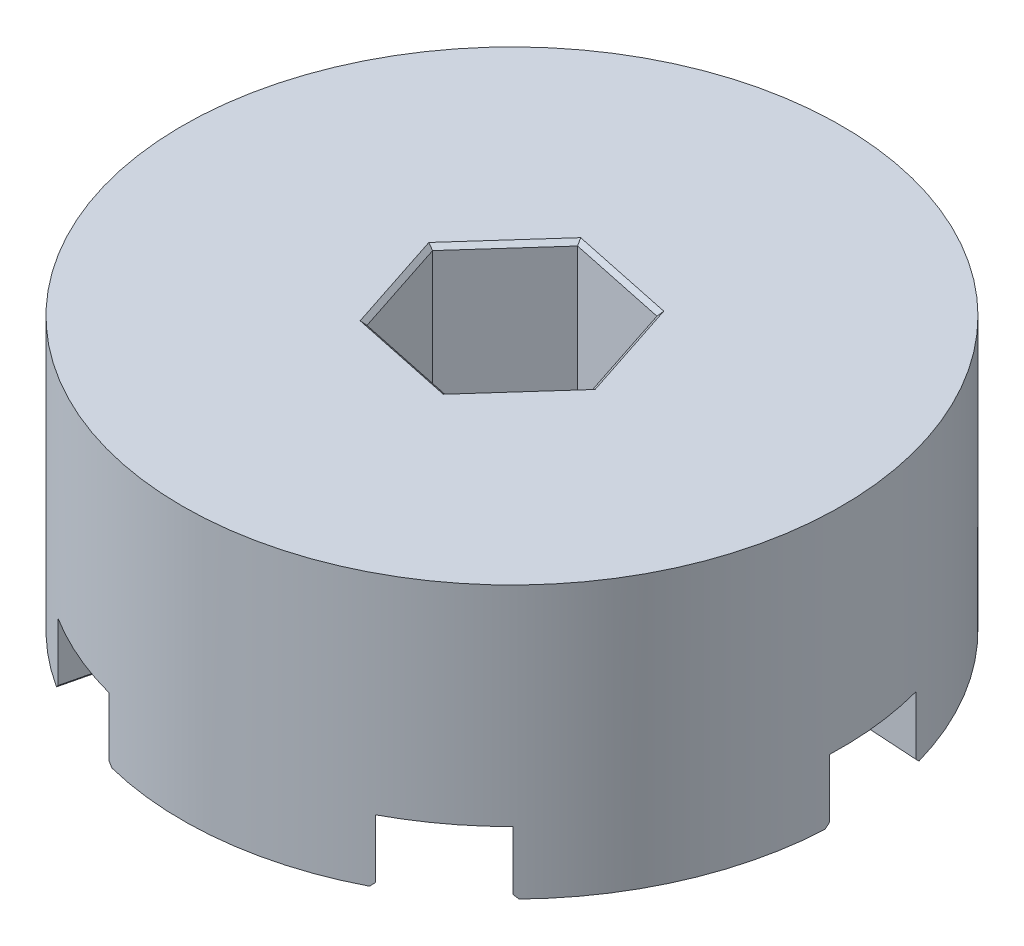
SolidWorks part; units mm, degrees
ref_plane "Front Plane" through (0, 0, 0) normal (0, 0, 1) x (1, 0, 0)
ref_plane "Top Plane" through (0, 0, 0) normal (0, 1, 0) x (1, 0, 0)
ref_plane "Right Plane" through (0, 0, 0) normal (1, 0, 0) x (0, 0, -1)
sketch "Sketch1" plane through (0, 0, 0) normal (0, 1, 0) x (1, 0, 0)
  circle A0 centre (0, 0) radius 15.75
  dimension "D1" = 31.5
extrude "Boss-Extrude1" add sketch "Sketch1" along normal blind 10
sketch "Sketch2" plane through (0, 10, 0) normal (0, 1, 0) x (1, 0, 0)
  line L1 (3.2747, 3.6551) -> (-1.5281, 4.6635)
  line L2 (-1.5281, 4.6635) -> (-4.8028, 1.0084)
  line L3 (-4.8028, 1.0084) -> (-3.2747, -3.6551)
  line L4 (-3.2747, -3.6551) -> (1.5281, -4.6635)
  line L5 (1.5281, -4.6635) -> (4.8028, -1.0084)
  line L6 (4.8028, -1.0084) -> (3.2747, 3.6551)
  circle A0 centre (0, 0) radius 4.25 construction
  dimension "D1" = 8.5
extrude "Cut-Extrude1" cut sketch "Sketch2" against normal blind 10
sketch "Sketch3" plane through (0, 0, 0) normal (0, -1, 0) x (1, 0, 0)
  line L0 (0, 0) -> (-29765.0204, -40175.161) construction
  line L1 (0, 0) -> (-19910.1998, 45864.8443) construction
  line L2 (0, 0) -> (49675.2202, -5689.6834) construction
  line L3 (0, 0) -> (-45864.8443, -19910.1998) construction
  line L4 (0, 0) -> (-7.1549, -3.106) construction
  line L5 (-7.1549, -3.106) -> (-22343.6343, -44736.5575) construction
  line L6 (-7.1549, -3.106) -> (-47939.6938, 14226.1498) construction
  line L7 (-7.1549, -3.106) -> (-11.1556, -11.1182)
  line L8 (-7.1549, -3.106) -> (-15.7401, -0.5574)
  line L9 (-6.2673, 4.6433) -> (-15.2065, 4.1019)
  line L10 (-6.2673, 4.6433) -> (-8.3528, 13.3527)
  line L11 (0.8876, 7.7493) -> (-4.0509, 15.2202)
  line L12 (0.8876, 7.7493) -> (7.3874, 13.91)
  line L13 (7.1549, 3.106) -> (11.1556, 11.1182)
  line L14 (7.1549, 3.106) -> (15.7401, 0.5574)
  line L15 (6.2673, -4.6433) -> (15.2065, -4.1019)
  line L16 (6.2673, -4.6433) -> (8.3528, -13.3527)
  line L17 (-0.8876, -7.7493) -> (4.0509, -15.2202)
  line L18 (-0.8876, -7.7493) -> (-7.3874, -13.91)
  circle A0 centre (0, 0) radius 15.75 construction
  arc A1 (-15.7401, -0.5574) -> (-11.1556, -11.1182) centre (0, 0) ccw
  arc A2 (-8.3528, 13.3527) -> (-15.2065, 4.1019) centre (0, 0) ccw
  arc A3 (7.3874, 13.91) -> (-4.0509, 15.2202) centre (0, 0) ccw
  arc A4 (15.7401, 0.5574) -> (11.1556, 11.1182) centre (0, 0) ccw
  arc A5 (8.3528, -13.3527) -> (15.2065, -4.1019) centre (0, 0) ccw
  arc A6 (-7.3874, -13.91) -> (4.0509, -15.2202) centre (0, 0) ccw
  point P43 (0, 0)
  circle M10 centre (0, 0) radius 15.75
  dimension "D1" = 60
  dimension "D2" = 60
  dimension "D3" = 30
  dimension "D4" = 7.8
  dimension "D5" = 40
  dimension "D6" = 40
  dimension "D7" = 6
extrude "Boss-Extrude2" add sketch "Sketch3" along normal blind 3 contours L7 L8 M10 | L17 L18 M10 | L15 L16 M10 | L13 L14 M10 | L11 L12 M10 | L9 L10 M10
chamfer "Chamfer1" distance 0.2 angle 45 18 edges at (-3.1654, 10, -2.8359) (-4.0387, 10, 1.3234) (-0.8733, 10, 4.1593) (3.1654, 10, 2.8359) (4.0387, 10, -1.3234) (0.8733, 10, -4.1593) (-7.31, -3, 8.998) (-10.7369, -3, 4.3726) (-11.4475, -3, -1.8317) (-9.1553, -3, -7.1121) (-4.1375, -3, -10.8297) (1.5816, -3, -11.4847) (7.31, -3, -8.998) (10.7369, -3, -4.3726) (11.4475, -3, 1.8317) (9.1553, -3, 7.1121) (-1.5816, -3, 11.4847) (4.1375, -3, 10.8297)
